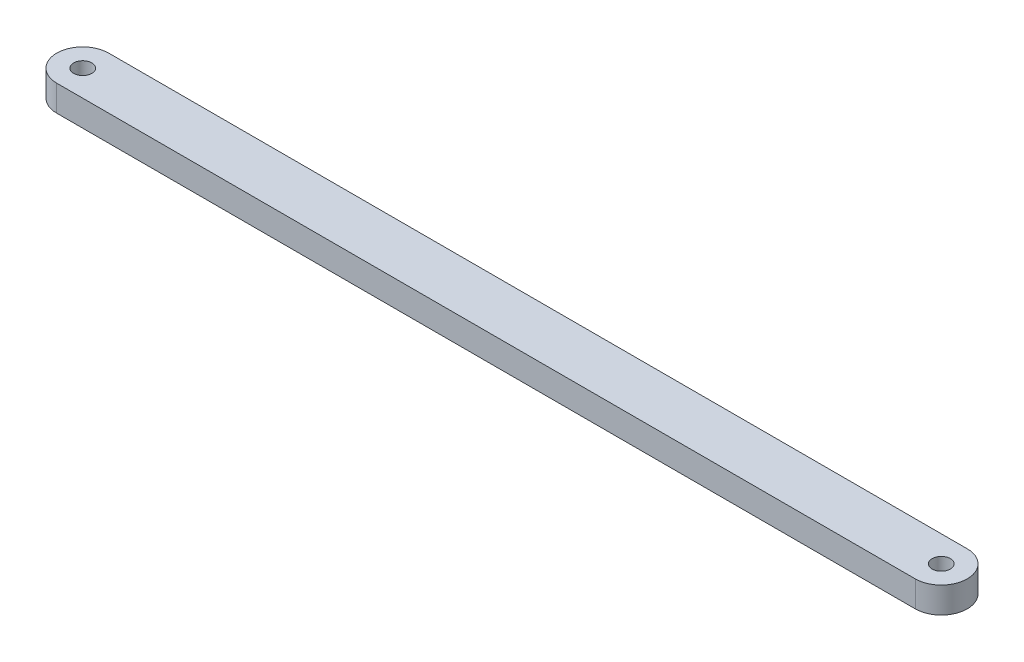
SolidWorks part; units mm, degrees
ref_plane "Front Plane" through (0, 0, 0) normal (0, 0, 1) x (1, 0, 0)
ref_plane "Top Plane" through (0, 0, 0) normal (0, 1, 0) x (1, 0, 0)
ref_plane "Right Plane" through (0, 0, 0) normal (1, 0, 0) x (0, 0, -1)
sketch "Sketch1" plane through (0, 0, 0) normal (0, 1, 0) x (1, 0, 0)
  line L0 (-165, 0) -> (165, 0) construction
  line L1 (-165, 10) -> (165, 10)
  line L2 (-165, -10) -> (165, -10)
  arc A0 (-165, 10) -> (-165, -10) centre (-165, 0) ccw
  arc A1 (165, -10) -> (165, 10) centre (165, 0) ccw
  circle A2 centre (-165, 0) radius 3.5
  circle A3 centre (165, 0) radius 3.5
  point P2 (0, 0)
  dimension "D3" = 7
  dimension "D4" = 7
  dimension "D1" = 330
  dimension "D2" = 20
extrude "Boss-Extrude1" add sketch "Sketch1" along normal blind 10
equation "\"D4@Sketch1\"=\"D3@Sketch1\""
